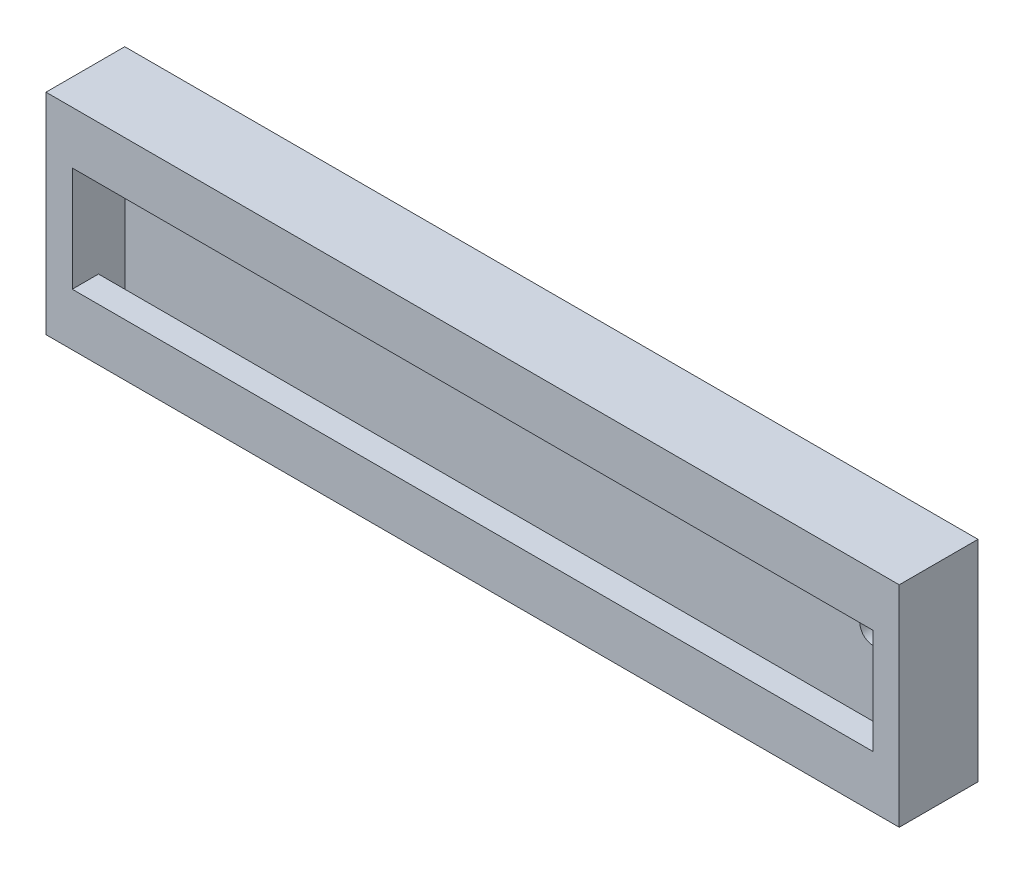
SolidWorks part; units mm, degrees
ref_plane "Front Plane" through (0, 0, 0) normal (0, 0, 1) x (1, 0, 0)
ref_plane "Top Plane" through (0, 0, 0) normal (0, 1, 0) x (1, 0, 0)
ref_plane "Right Plane" through (0, 0, 0) normal (1, 0, 0) x (0, 0, -1)
sketch "Sketch1" plane through (0, 0, 0) normal (0, 0, 1) x (1, 0, 0)
  line L1 (-32.5, -8) -> (32.5, -8)
  line L2 (-32.5, -8) -> (-32.5, 8)
  line L3 (-32.5, 8) -> (32.5, 8)
  line L4 (32.5, -8) -> (32.5, 8)
  line L5 (-32.5, -8) -> (32.5, 8) construction
  line L6 (-32.5, 8) -> (32.5, -8) construction
  point P0 (0, 0)
  dimension "D1" = 65
  dimension "D2" = 16
extrude "Boss-Extrude1" add sketch "Sketch1" along normal blind 2
sketch "Sketch2" plane through (0, 0, 2) normal (0, 0, 1) x (1, 0, 0)
  line L1 (-32.5, 8) -> (32.5, 8)
  line L2 (-32.5, 8) -> (-32.5, -8)
  line L3 (-32.5, -8) -> (32.5, -8)
  line L4 (32.5, 8) -> (32.5, -8)
  line L5 (-32.5, 8) -> (32.5, -8) construction
  line L6 (-32.5, -8) -> (32.5, 8) construction
  line L7 (-30.5, 6) -> (30.5, 6)
  line L8 (-30.5, 6) -> (-30.5, -6)
  line L9 (-30.5, -6) -> (30.5, -6)
  line L10 (30.5, 6) -> (30.5, -6)
  line L11 (-30.5, 6) -> (30.5, -6) construction
  line L12 (-30.5, -6) -> (30.5, 6) construction
  point P0 (0, 0)
  point P7 (0, 0)
  dimension "D1" = 2
  dimension "D2" = 2
extrude "Boss-Extrude2" add sketch "Sketch2" along normal blind 2
sketch "Sketch4" plane through (0, 0, 4) normal (0, 0, 1) x (1, 0, 0)
  line L0 (30.5, -6) -> (30.5, 6) construction
  line L1 (-32.5, 8) -> (32.5, 8)
  line L2 (-32.5, 8) -> (-32.5, -8)
  line L3 (-32.5, -8) -> (32.5, -8)
  line L4 (32.5, 8) -> (32.5, -8)
  line L5 (-32.5, 8) -> (32.5, -8) construction
  line L6 (-32.5, -8) -> (32.5, 8) construction
  line L7 (-30.5, 4) -> (30.5, 4)
  line L8 (-30.5, 4) -> (-30.5, -4)
  line L9 (-30.5, -4) -> (30.5, -4)
  line L10 (30.5, 4) -> (30.5, -4)
  line L11 (-30.5, 4) -> (30.5, -4) construction
  line L12 (-30.5, -4) -> (30.5, 4) construction
  line L13 (30.5, 6) -> (-30.5, 6) construction
  point P0 (0, 0)
  point P7 (0, 0)
  dimension "D1" = 2
extrude "Boss-Extrude3" add sketch "Sketch4" along normal blind 2
sketch "Sketch6" plane through (0, 0, 2) normal (0, 0, 1) x (1, 0, 0)
  line L0 (32.5, -8) -> (32.5, 8) construction
  line L1 (-32.5, -8) -> (32.5, -8) construction
  circle A0 centre (26.5, 0) radius 1
  dimension "D1" = 2
  dimension "D3" = 8
  dimension "D2" = 6
extrude "Cut-Extrude2" cut sketch "Sketch6" against normal through all
